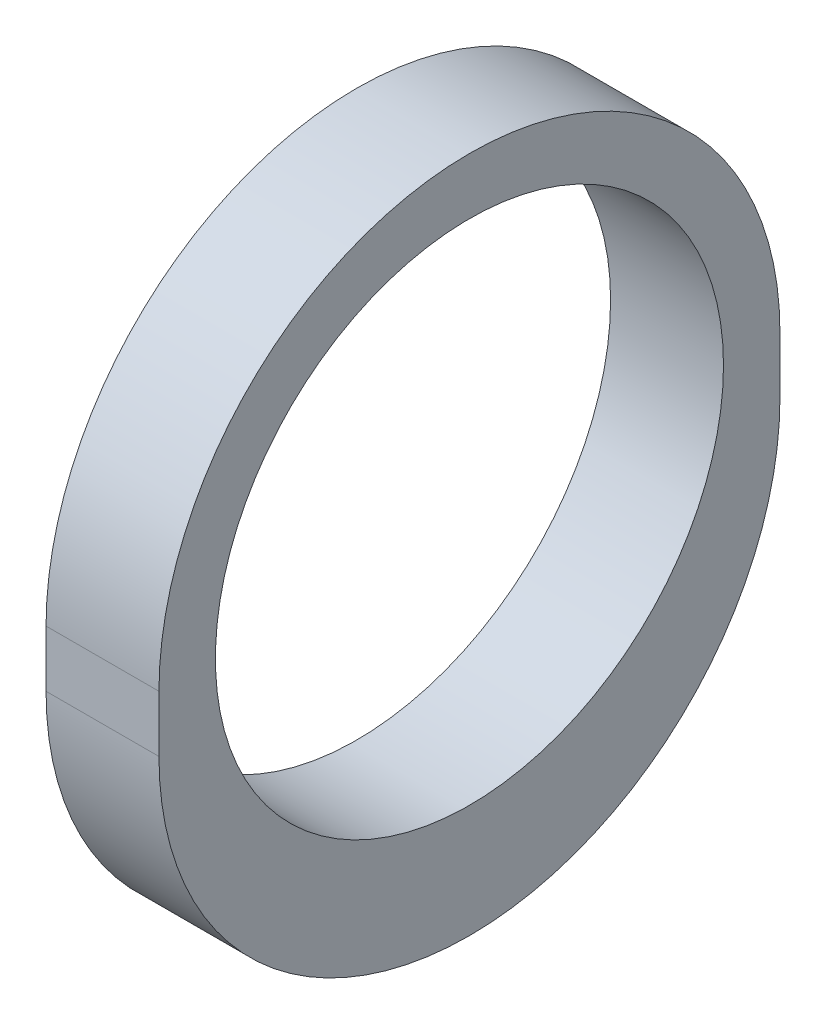
SolidWorks part; units mm, degrees
ref_plane "Piano frontale" through (0, 0, 0) normal (0, 0, 1) x (1, 0, 0)
ref_plane "Piano superiore" through (0, 0, 0) normal (0, 1, 0) x (1, 0, 0)
ref_plane "Piano destro" through (0, 0, 0) normal (1, 0, 0) x (0, 0, -1)
sketch "Schizzo1" plane through (0, 0, 0) normal (1, 0, 0) x (0, 0, -1)
  line L0 (0, -13) -> (0, 11) construction
  line L1 (-11, 0) -> (11, 0) construction
  line L2 (-11, 0) -> (-11, -2)
  line L3 (11, 0) -> (11, -2)
  circle A0 centre (0, 0) radius 9
  arc A1 (11, 0) -> (-11, 0) centre (0, 0) ccw
  arc A2 (-11, -2) -> (11, -2) centre (0, -2) ccw
  point P7 (0, 0)
  point P10 (0, 0)
  dimension "D1" = 18
  dimension "D2" = 11
  dimension "D3" = 2
extrude "Estrusione-Estrusione1" add sketch "Schizzo1" along normal mid plane 4
